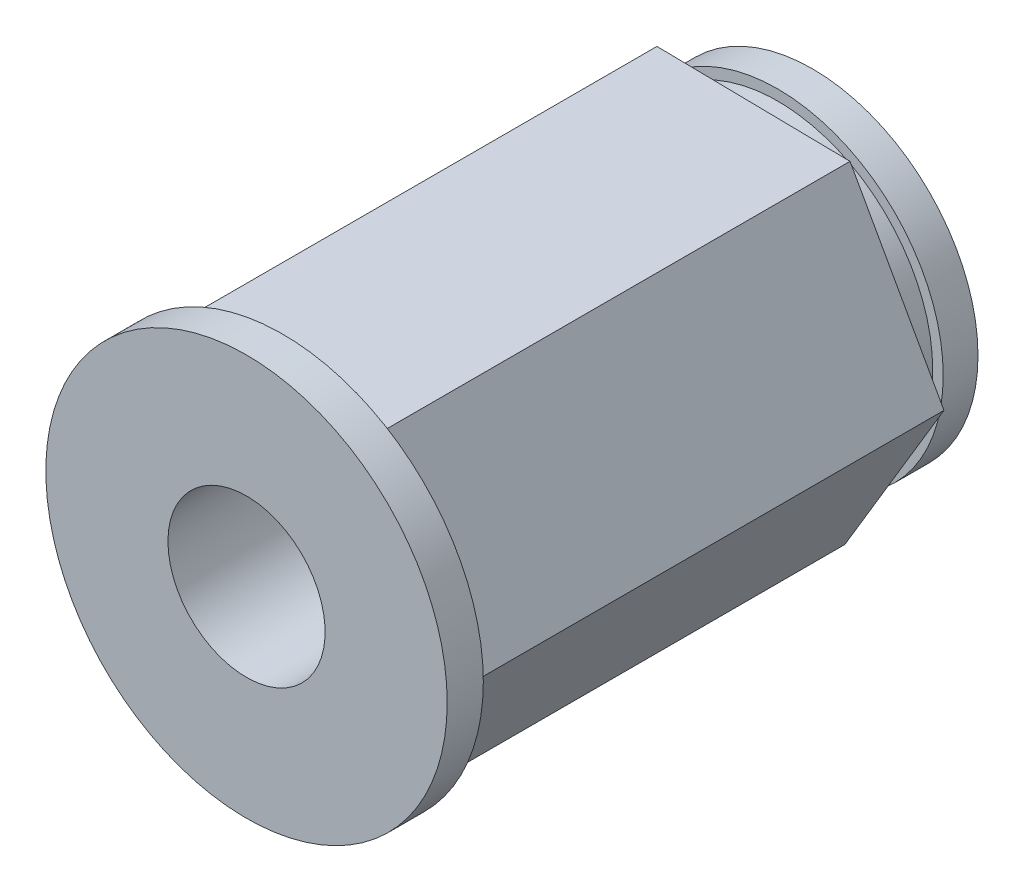
SolidWorks part; units mm, degrees
ref_plane "Front Plane" through (0, 0, 0) normal (0, 0, 1) x (1, 0, 0)
ref_plane "Top Plane" through (0, 0, 0) normal (0, 1, 0) x (1, 0, 0)
ref_plane "Right Plane" through (0, 0, 0) normal (1, 0, 0) x (0, 0, -1)
sketch "Sketch1" plane through (0, 0, 0) normal (0, 0, 1) x (1, 0, 0)
  line L1 (3.7638, 6.2926) -> (-3.5677, 6.4059)
  line L2 (-3.5677, 6.4059) -> (-7.3315, 0.1132)
  line L3 (-7.3315, 0.1132) -> (-3.7638, -6.2926)
  line L4 (-3.7638, -6.2926) -> (3.5677, -6.4059)
  line L5 (3.5677, -6.4059) -> (7.3315, -0.1132)
  line L6 (7.3315, -0.1132) -> (3.7638, 6.2926)
  circle A0 centre (0, 0) radius 6.35 construction
  dimension "D1" = 12.7
extrude "Boss-Extrude1" add sketch "Sketch1" along normal blind 8.89 and the other way blind 8.89
sketch "Sketch2" plane through (0, 0, 8.89) normal (0, 0, 1) x (1, 0, 0)
  circle A0 centre (0, 0) radius 7.62
  dimension "D1" = 15.24
extrude "Boss-Extrude3" add sketch "Sketch2" along normal blind 1.3716
sketch "Sketch4" plane through (0, 0, -8.89) normal (0, 0, -1) x (-1, 0, 0)
  circle A0 centre (0, 0) radius 5.8865
  dimension "D1" = 11.7729
extrude "Boss-Extrude4" add sketch "Sketch4" along normal blind 1.016
sketch "Sketch5" plane through (0, 0, -9.906) normal (0, 0, -1) x (-1, 0, 0)
  circle A0 centre (0, 0) radius 6.2865
  dimension "D1" = 12.573
extrude "Boss-Extrude5" add sketch "Sketch5" along normal blind 1.3208
sketch "Sketch6" plane through (0, 0, -11.2268) normal (0, 0, -1) x (-1, 0, 0)
  circle A0 centre (0, 0) radius 2.9845
  dimension "D1" = 5.969
extrude "Cut-Extrude2" cut sketch "Sketch6" against normal through all
